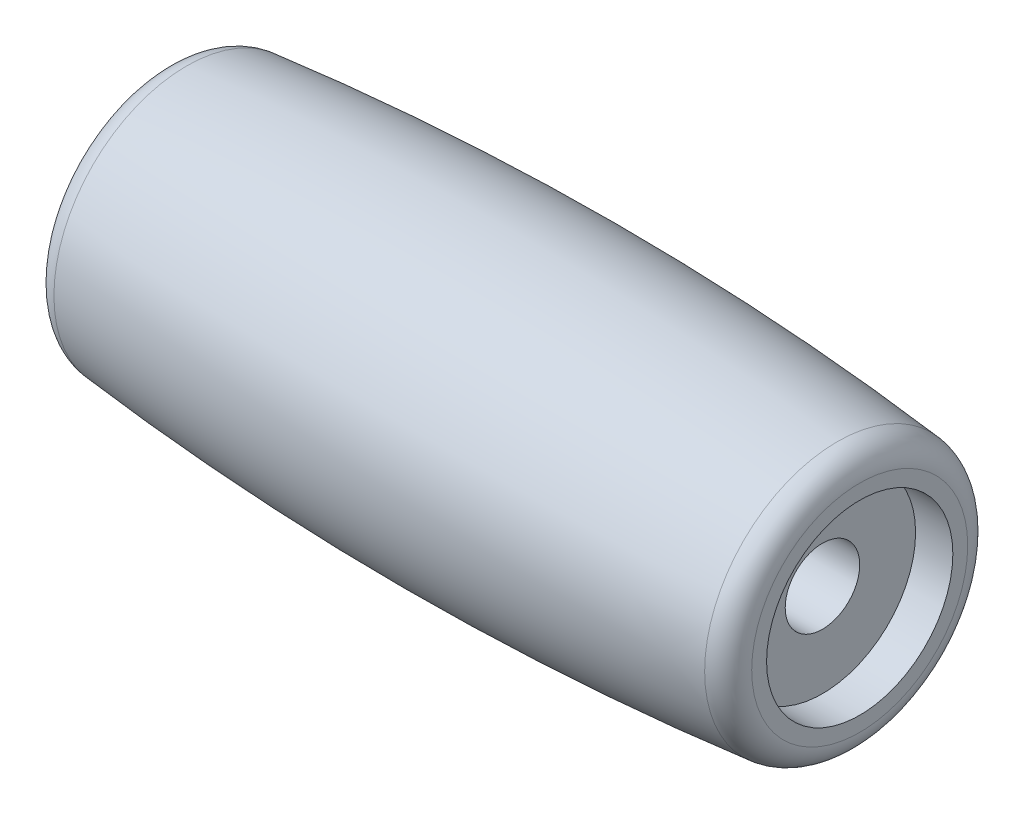
SolidWorks part; units mm, degrees
ref_plane "Front Plane" through (0, 0, 0) normal (0, 0, 1) x (1, 0, 0)
ref_plane "Top Plane" through (0, 0, 0) normal (0, 1, 0) x (1, 0, 0)
ref_plane "Right Plane" through (0, 0, 0) normal (1, 0, 0) x (0, 0, -1)
sketch "Sketch1" plane through (0, 0, 0) normal (0, 1, 0) x (1, 0, 0)
  line L3 (22.5607, 12.4965) -> (50.5607, 12.4965) construction
  line L9 (36.5607, 22.1635) -> (36.5607, 0.8961) construction
  line L10 (49.0607, 16.2465) -> (49.0607, 13.9965)
  line L11 (22.5607, 16.2465) -> (24.0607, 16.2465)
  line L12 (24.0607, 16.2465) -> (24.0607, 13.9965)
  line L13 (50.5607, 16.2465) -> (49.0607, 16.2465)
  line L14 (24.0607, 13.9965) -> (49.0607, 13.9965)
  line L16 (22.5607, 16.2465) -> (22.5607, 16.8451)
  line L17 (50.5607, 16.2465) -> (50.5607, 16.8451)
  arc A0 (23.4607, 17.8401) -> (49.6606, 17.8401) centre (36.5607, -112.5452) cw
  arc A1 (50.5607, 16.8451) -> (49.6606, 17.8401) centre (49.5607, 16.8451) ccw
  arc A2 (22.5607, 16.8451) -> (23.4607, 17.8401) centre (23.5607, 16.8451) cw
  dimension "D4" = 1.5
  dimension "D1" = 28
  dimension "D3" = 1
  dimension "D2" = 2.25
  dimension "D5" = 1.5
revolve "Revolve2" add sketch "Sketch1" angle 360 about L3
